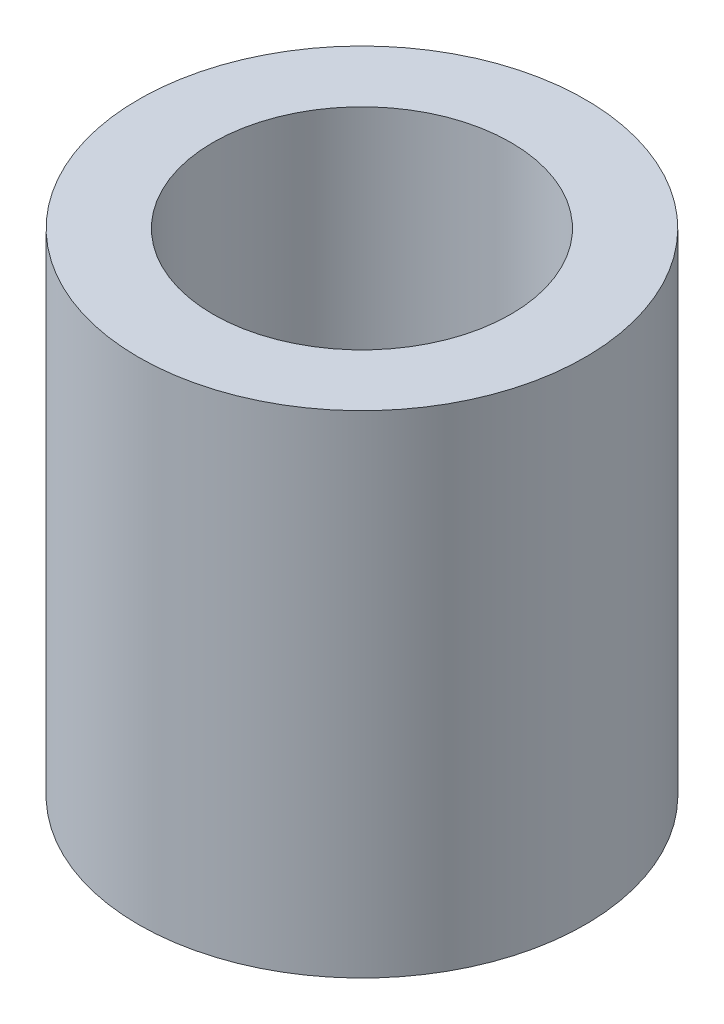
SolidWorks part; units mm, degrees
material "ABS"
ref_plane "Front Plane" through (0, 0, 0) normal (0, 0, 1) x (1, 0, 0)
ref_plane "Top Plane" through (0, 0, 0) normal (0, 1, 0) x (1, 0, 0)
ref_plane "Right Plane" through (0, 0, 0) normal (1, 0, 0) x (0, 0, -1)
sketch "Sketch1" plane through (0, 0, 0) normal (0, 1, 0) x (1, 0, 0)
  circle A0 centre (0, 0) radius 9.525
  circle A2 centre (0, 0) radius 6.35
  dimension "D2" = 19.05
extrude "Boss-Extrude1" add sketch "Sketch1" along normal blind 20.955
